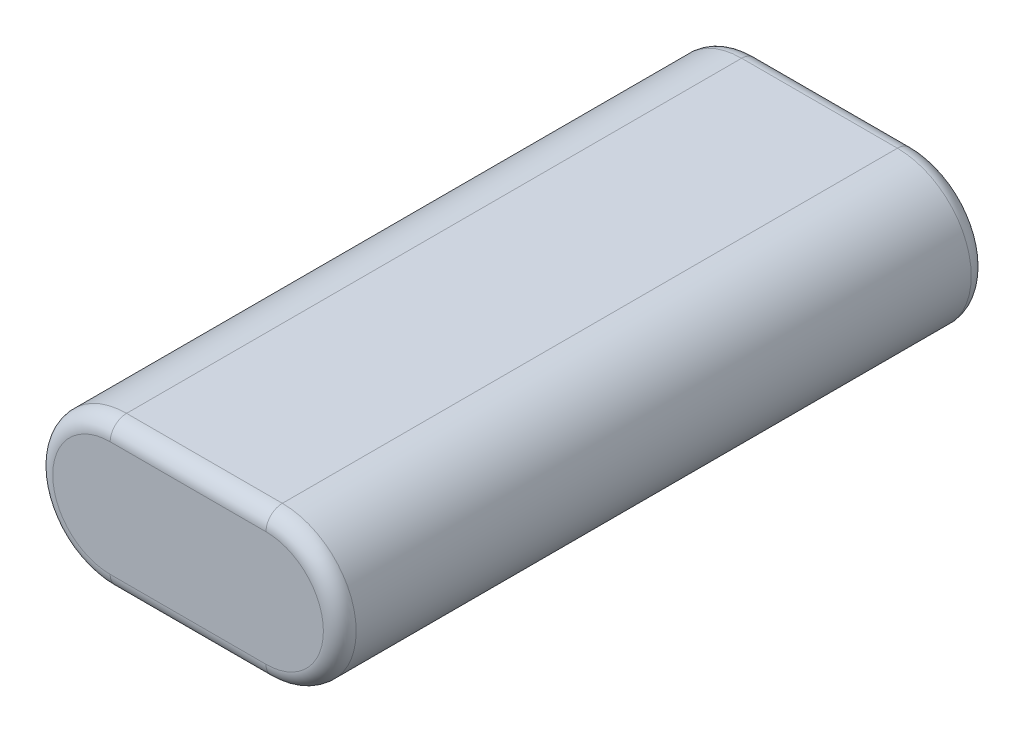
SolidWorks part; units mm, degrees
ref_plane "Front Plane" through (0, 0, 0) normal (0, 0, 1) x (1, 0, 0)
ref_plane "Top Plane" through (0, 0, 0) normal (0, 1, 0) x (1, 0, 0)
ref_plane "Right Plane" through (0, 0, 0) normal (1, 0, 0) x (0, 0, -1)
sketch "Sketch1" plane through (0, 0, 0) normal (0, 0, 1) x (1, 0, 0)
  line L1 (0, 9) -> (19, 9)
  line L2 (0, 9) -> (0, 0)
  line L3 (0, 0) -> (19, 0)
  line L4 (19, 9) -> (19, 0)
  line L5 (0, 0) -> (19, 0)
  line L6 (0, 0) -> (0, -9)
  line L7 (0, -9) -> (19, -9)
  line L8 (19, 0) -> (19, -9)
  circle A0 centre (0, 0) radius 9
  circle A1 centre (19, 0) radius 9
  dimension "D1" = 18
  dimension "D2" = 19
extrude "Boss-Extrude1" add sketch "Sketch1" along normal blind 79 contours L2 A0 L6 | L3 A0 L2 | A1 L1 A0 L5 | L4 A1 L3 | L8 A1 L4 | L3 A1 L8 | A1 L5 A0 L7 | L6 A0 L3
fillet "Fillet1" radius 2 8 edges at (-9, 0, 0) (-9, 0, 79) (9.5, -9, 0) (9.5, -9, 79) (28, 0, 0) (28, 0, 79) (9.5, 9, 0) (9.5, 9, 79)
